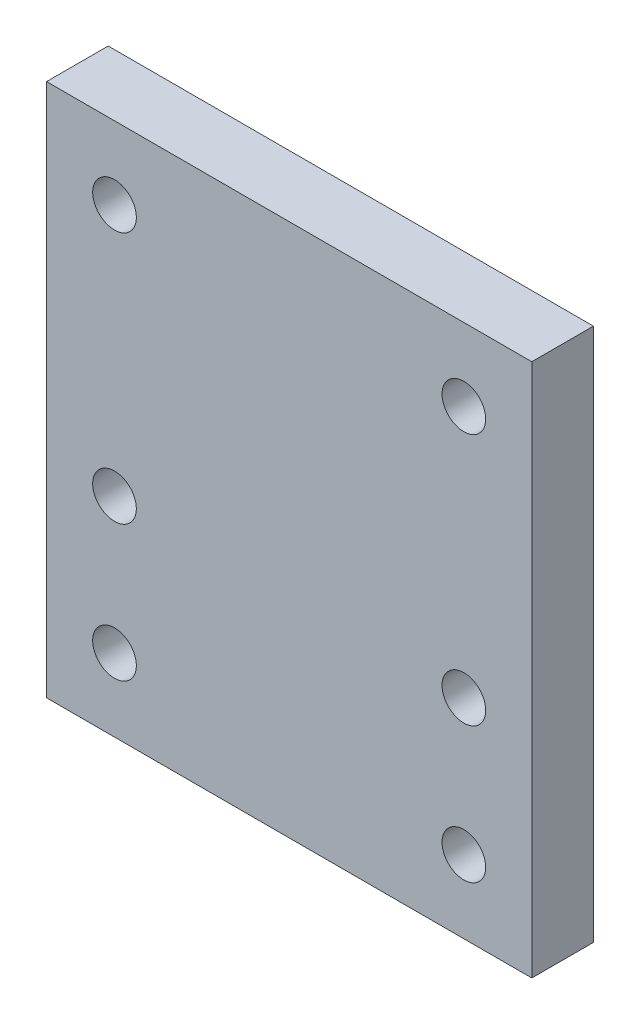
SolidWorks part; units mm, degrees
ref_plane "Alzado" through (0, 0, 0) normal (0, 0, 1) x (1, 0, 0)
ref_plane "Planta" through (0, 0, 0) normal (0, 1, 0) x (1, 0, 0)
ref_plane "Vista lateral" through (0, 0, 0) normal (1, 0, 0) x (0, 0, -1)
sketch "Sketch1" plane through (0, 0, 0) normal (0, 0, 1) x (1, 0, 0)
  line L1 (0, 0) -> (100, 0)
  line L2 (0, 0) -> (0, 110)
  line L3 (0, 110) -> (100, 110)
  line L4 (100, 0) -> (100, 110)
  dimension "D1" = 100
  dimension "D2" = 110
extrude "Boss-Extrude1" add sketch "Sketch1" along normal blind 12.7
sketch "Sketch2" plane through (0, 0, 12.7) normal (0, 0, 1) x (1, 0, 0)
  line L0 (100, 110) -> (0, 110) construction
  line L1 (100, 0) -> (86, 0) construction
  line L2 (0, 0) -> (100, 0) construction
  line L3 (86, 0) -> (86, 15) construction
  line L4 (0, 110) -> (0, 0) construction
  line L5 (0, 0) -> (14, 0) construction
  line L6 (14, 0) -> (14, 15) construction
  line L7 (100, 30) -> (0, 30) construction
  line L31 (100, -5.8) -> (100, 104.2) construction
  circle A0 centre (86, 15) radius 4.5
  circle A1 centre (14, 15) radius 4.5
  arc A4 (18.5, 43) -> (9.5, 43) centre (14, 43) ccw
  arc A5 (9.5, 43) -> (18.5, 43) centre (14, 43) ccw
  arc A6 (18.5, 95) -> (9.5, 95) centre (14, 95) ccw
  arc A7 (9.5, 95) -> (18.5, 95) centre (14, 95) ccw
  arc A12 (90.5, 43) -> (81.5, 43) centre (86, 43) ccw
  arc A13 (81.5, 43) -> (90.5, 43) centre (86, 43) ccw
  arc A14 (90.5, 95) -> (81.5, 95) centre (86, 95) ccw
  arc A15 (81.5, 95) -> (90.5, 95) centre (86, 95) ccw
  point P30 (50, 110)
  dimension "D14" = 9
  dimension "D15" = 9
  dimension "D3" = 15
  dimension "D4" = 14
  dimension "D5" = 14
  dimension "D6" = 15
  dimension "D7" = 14
  dimension "D8" = 15
  dimension "D9" = 14
  dimension "D10" = 52
  dimension "D11" = 52
  dimension "D12" = 72
  dimension "D2" = 72
  dimension "D13" = 15
  dimension "D16" = 28
  dimension "D17" = 30
extrude "Cut-Extrude1" cut sketch "Sketch2" against normal up to surface (12.7 mm away) contours A12 A13 | A14 A15 | A6 A7 | A4 A5 | A0 | A1 up to face at (50, 55, 0)
